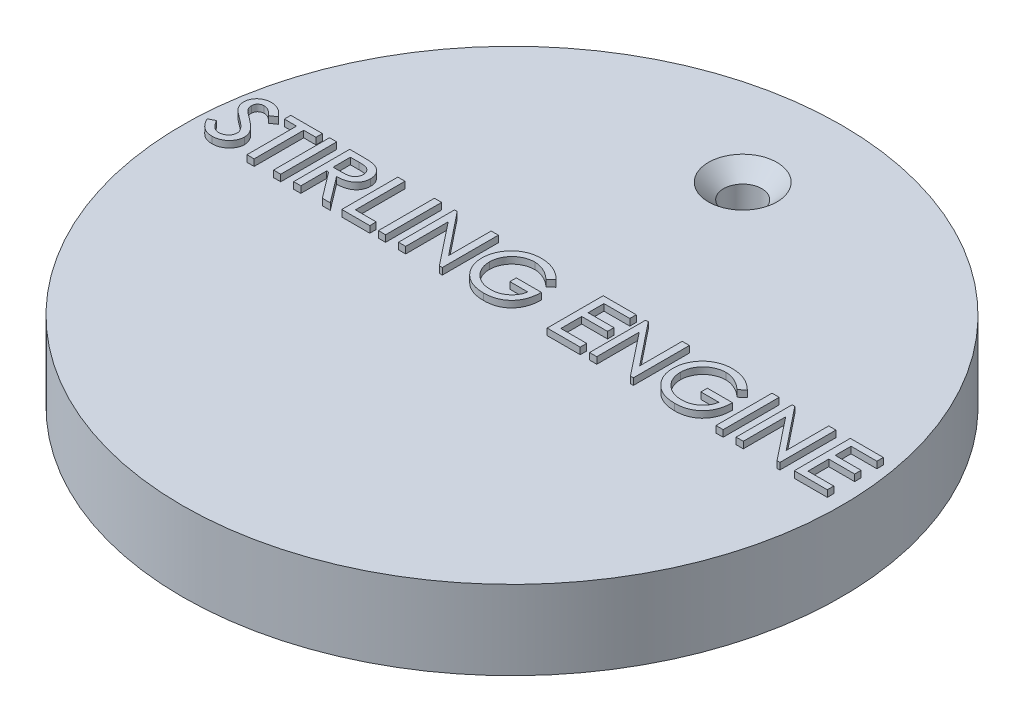
SolidWorks part; units mm, degrees
ref_plane "Front Plane" through (0, 0, 0) normal (0, 0, 1) x (1, 0, 0)
ref_plane "Top Plane" through (0, 0, 0) normal (0, 1, 0) x (1, 0, 0)
ref_plane "Right Plane" through (0, 0, 0) normal (1, 0, 0) x (0, 0, -1)
sketch "Sketch1" plane through (0, 0, 0) normal (0, 1, 0) x (1, 0, 0)
  circle A0 centre (0, 0) radius 50
  dimension "D1" = 100
extrude "Boss-Extrude1" add sketch "Sketch1" along normal blind 12
sketch "Sketch2" plane through (0, 12, 0) normal (0, 1, 0) x (1, 0, 0)
  line L0 (-50, 0) -> (50, 0) construction
  circle A0 centre (0, 0) radius 50 construction
  text T0 "STIRLING ENGINE" font "Century Gothic" height 8.5
extrude "Boss-Extrude2" add sketch "Sketch2" along normal blind 1
hole_wizard "CSK for M5 Flat Head Machine Screw1" positions "Sketch3" profile "Sketch4" countersink size "M5" standard "ANSI Metric" end condition through all
sketch "Sketch3" plane through (0, 12, 0) normal (0, 1, 0) x (1, 0, 0)
  point P0 (0, 35)
  dimension "D1" = 35
sketch "Sketch4" plane through (0, 12, -35) normal (1, 0, 0) x (0, 0, 1)
  line L0 (0, 0) -> (0, 12)
  line L1 (0, 12) -> (2.9, 12)
  line L2 (2.9, 12) -> (2.9, 2.3)
  line L3 (2.9, 2.3) -> (5.2, 0)
  line L5 (5.2, 0) -> (0, 0)
  line L6 (-2.9, 2.3) -> (-5.2, 0) construction
  line L11 (0, -6.35) -> (0, 107.95) construction
  dimension "Thru Hole Dia." = 5.8
  dimension "Thru Hole Depth" = 12
  dimension "Near C'Sink Dia." = 10.4
  dimension "Near C'Sink Angle" = 90
